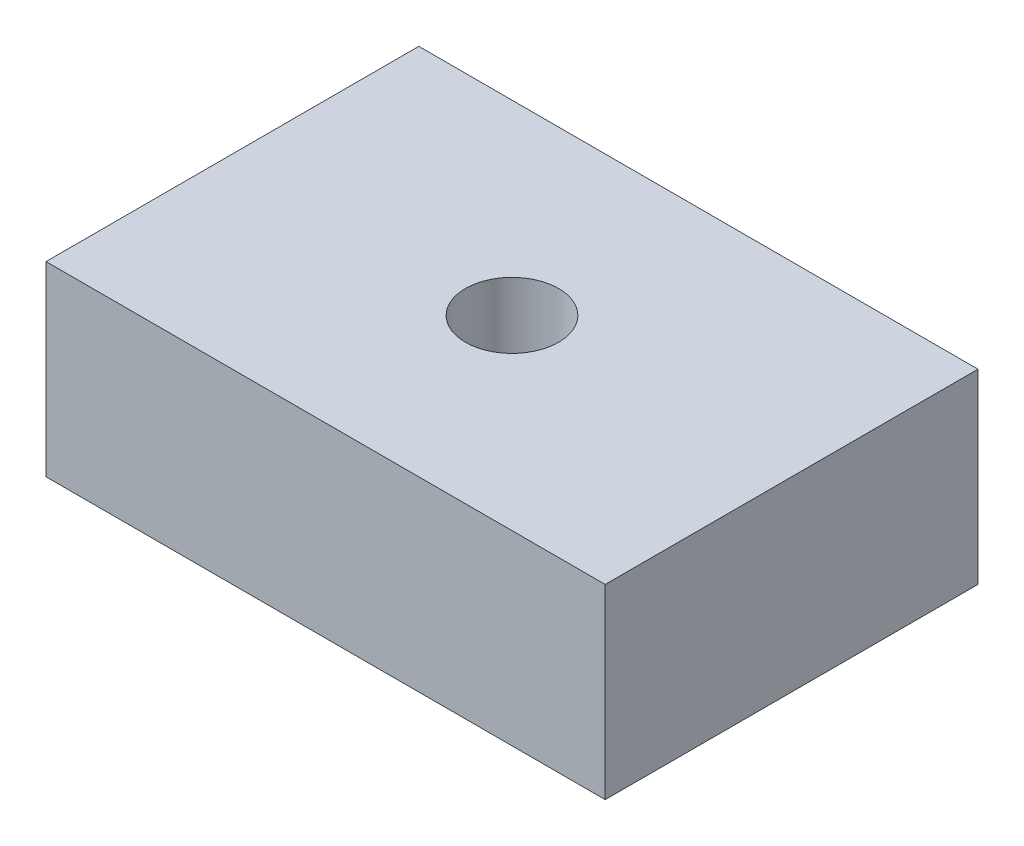
SolidWorks part; units mm, degrees
material "AISI 316 Annealed Stainless Steel Bar (SS)"
ref_plane "Front Plane" through (0, 0, 0) normal (0, 0, 1) x (1, 0, 0)
ref_plane "Top Plane" through (0, 0, 0) normal (0, 1, 0) x (1, 0, 0)
ref_plane "Right Plane" through (0, 0, 0) normal (1, 0, 0) x (0, 0, -1)
sketch "Sketch1" plane through (0, 0, 0) normal (0, 1, 0) x (1, 0, 0)
  line L1 (-15, -10) -> (15, -10)
  line L2 (-15, -10) -> (-15, 10)
  line L3 (-15, 10) -> (15, 10)
  line L4 (15, -10) -> (15, 10)
  line L5 (-15, -10) -> (15, 10) construction
  line L6 (-15, 10) -> (15, -10) construction
  circle A0 centre (0, 0) radius 2.5
  point P0 (0, 0)
  dimension "D3" = 5
  dimension "D1" = 20
  dimension "D2" = 30
extrude "Boss-Extrude1" add sketch "Sketch1" along normal blind 10
